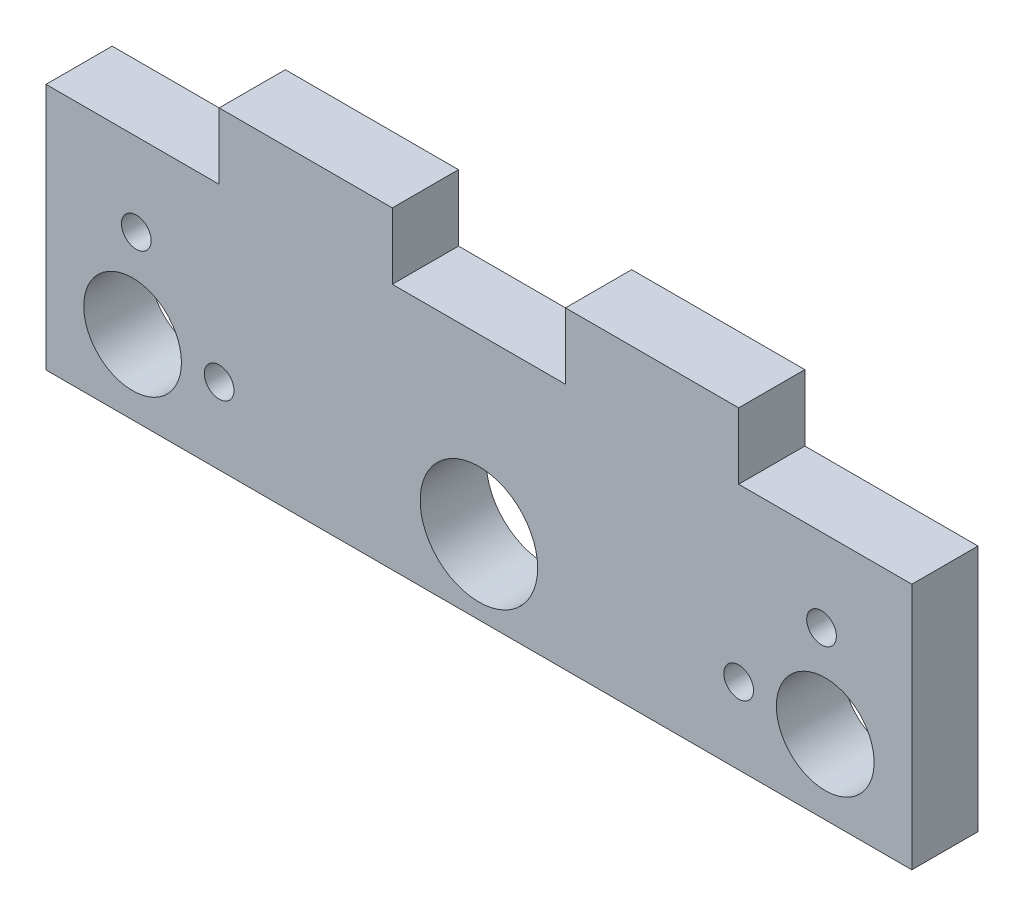
SolidWorks part; units mm, degrees
ref_plane "Front Plane" through (0, 0, 0) normal (0, 0, 1) x (1, 0, 0)
ref_plane "Top Plane" through (0, 0, 0) normal (0, 1, 0) x (1, 0, 0)
ref_plane "Right Plane" through (0, 0, 0) normal (1, 0, 0) x (0, 0, -1)
sketch "Model" plane through (0, 0, 0) normal (0, 0, 1) x (1, 0, 0)
  line L0 (0, 0) -> (0, 20) construction
  line L1 (-35, 0) -> (35, 0)
  line L2 (-35, 0) -> (-35, 20)
  line L3 (-35, 20) -> (-21, 20)
  line L4 (35, 0) -> (35, 20)
  line L5 (21, 20) -> (21, 25.35)
  line L6 (-21, 20) -> (-21, 25.35)
  line L7 (-21, 25.35) -> (-7, 25.35)
  line L8 (-7, 20) -> (-7, 25.35)
  line L9 (-7, 20) -> (7, 20)
  line L10 (7, 20) -> (7, 25.35)
  line L11 (21, 25.35) -> (7, 25.35)
  line L12 (21, 20) -> (35, 20)
  circle A0 centre (0, 6) radius 4.75
  circle A1 centre (-28, 6) radius 3.95
  circle A2 centre (-27.7, 13.3) radius 1.2
  circle A3 centre (-21, 6.16) radius 1.2
  circle A4 centre (21, 6.16) radius 1.2
  circle A5 centre (28, 6) radius 3.95
  circle A6 centre (27.7, 13.3) radius 1.2
  dimension "D13" = 9.5
  dimension "D16" = 7.9
  dimension "D21" = 2.4
  dimension "D1" = 70
  dimension "D2" = 20
  dimension "D7" = 5.35
  dimension "D9" = 14
  dimension "D11" = 7
  dimension "D14" = 6
  dimension "D18" = 6
  dimension "D20" = 7
  dimension "D27" = 7.3
  dimension "D30" = 7
  dimension "D31" = 6.16
  dimension "D25" = 7.3
extrude "Boss-Extrude1" add sketch "Model" along normal blind 5.35
equation "\"mdfthick\"=5.35"
equation "\"D7@Model\"=\"mdfthick\""
equation "\"D1@Boss-Extrude1\"=\"mdfthick\""
